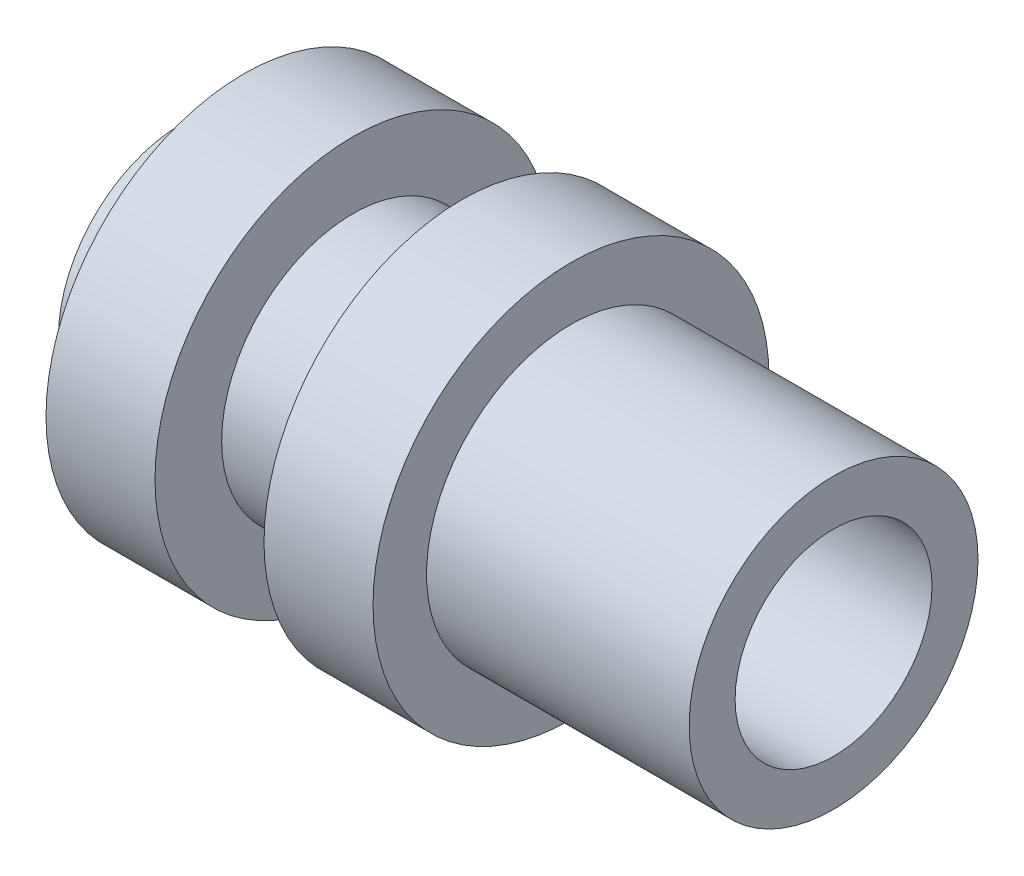
SolidWorks part; units mm, degrees
ref_plane "Front Plane" through (0, 0, 0) normal (0, 0, 1) x (1, 0, 0)
ref_plane "Top Plane" through (0, 0, 0) normal (0, 1, 0) x (1, 0, 0)
ref_plane "Right Plane" through (0, 0, 0) normal (1, 0, 0) x (0, 0, -1)
sketch "Sketch1" plane through (0, 0, 0) normal (1, 0, 0) x (0, 0, -1)
  circle A0 centre (0, 0) radius 15.0762
  dimension "D1" = 30.1523
extrude "Boss-Extrude1" add sketch "Sketch1" along normal blind 24.9072
sketch "Sketch2" plane through (0, 0, 0) normal (-1, 0, 0) x (0, 0, 1)
  circle A0 centre (0, 0) radius 4.5847
  circle A1 centre (0, 0) radius 9.3853
  dimension "D1" = 18.7706
  dimension "D2" = 9.1694
extrude "Boss-Extrude2" add sketch "Sketch2" along normal blind 4.7498
sketch "Sketch3" plane through (24.9072, 0, 0) normal (1, 0, 0) x (0, 0, -1)
  circle A0 centre (0, 0) radius 7.5
  dimension "D1" = 15
extrude "Cut-Extrude1" cut sketch "Sketch3" against normal blind 18.75
sketch "Sketch4" plane through (24.9072, 0, 0) normal (1, 0, 0) x (0, 0, -1)
  circle A0 centre (0, 0) radius 11
  circle A1 centre (0, 0) radius 7.5
  circle A2 centre (0, 0) radius 7.5 construction
  dimension "D1" = 22
extrude "Boss-Extrude3" add sketch "Sketch4" along normal blind 20
ref_plane "Plane1" through (16.6048, 0, 0) normal (1, 0, 0) x (0, 0, -1)
sketch "Sketch5" plane through (16.6048, 0, 0) normal (1, 0, 0) x (0, 0, -1)
  circle A1 centre (0, 0) radius 15.0762
  circle A2 centre (0, 0) radius 15.0762 construction
  circle A4 centre (0, 0) radius 10
  dimension "D1" = 20
extrude "Cut-Extrude4" cut sketch "Sketch5" against normal blind 8.3024
